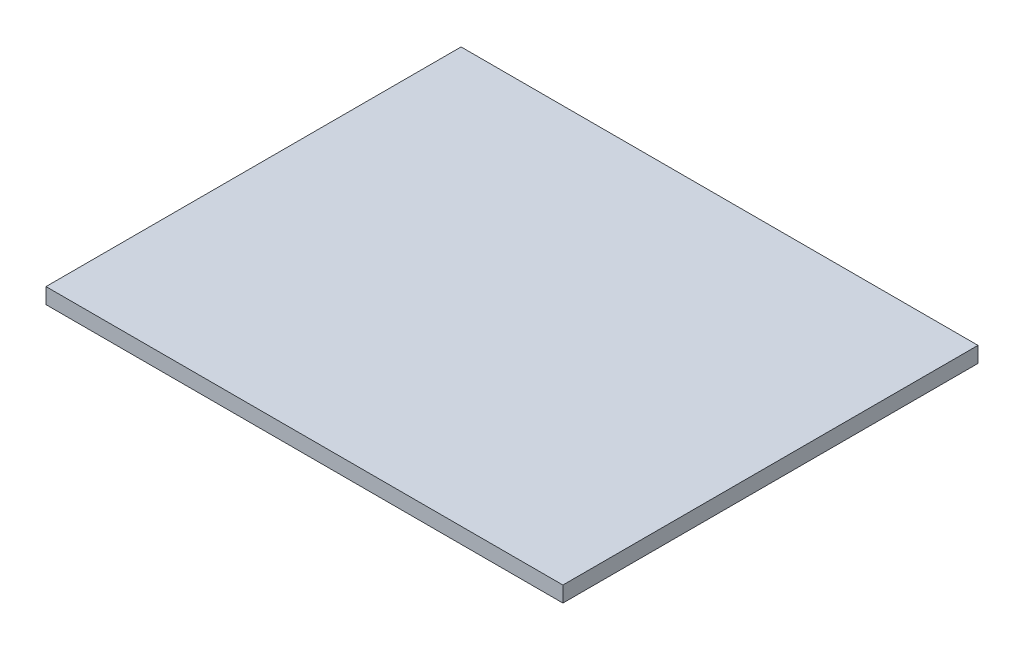
SolidWorks part; units mm, degrees
ref_plane "Front Plane" through (0, 0, 0) normal (0, 0, 1) x (1, 0, 0)
ref_plane "Top Plane" through (0, 0, 0) normal (0, 1, 0) x (1, 0, 0)
ref_plane "Right Plane" through (0, 0, 0) normal (1, 0, 0) x (0, 0, -1)
sketch "Sketch1" plane through (0, 0, 0) normal (0, 0, 1) x (1, 0, 0)
  line L1 (0, 0) -> (66, 0)
  line L2 (0, 0) -> (0, 2)
  line L3 (0, 2) -> (66, 2)
  line L4 (66, 0) -> (66, 2)
  dimension "D1" = 66
  dimension "D2" = 2
extrude "Profile" add sketch "Sketch1" along normal blind 53
equation "\"Profile_Depth\" = 53mm"
equation "\"D1@Profile\" = \"Profile_Depth\""
equation "\"Profile_Sketch_1\"= 66mm"
equation "\"D1@Sketch1\" = \"Profile_Sketch_1\""
equation "\"Profile_Sketch_2\"= 2mm"
equation "\"D2@Sketch1\" = \"Profile_Sketch_2\""
equation "\"EnvelopeWidth\"= 66mm"
equation "\"EnvelopeHeight\"= 2mm"
